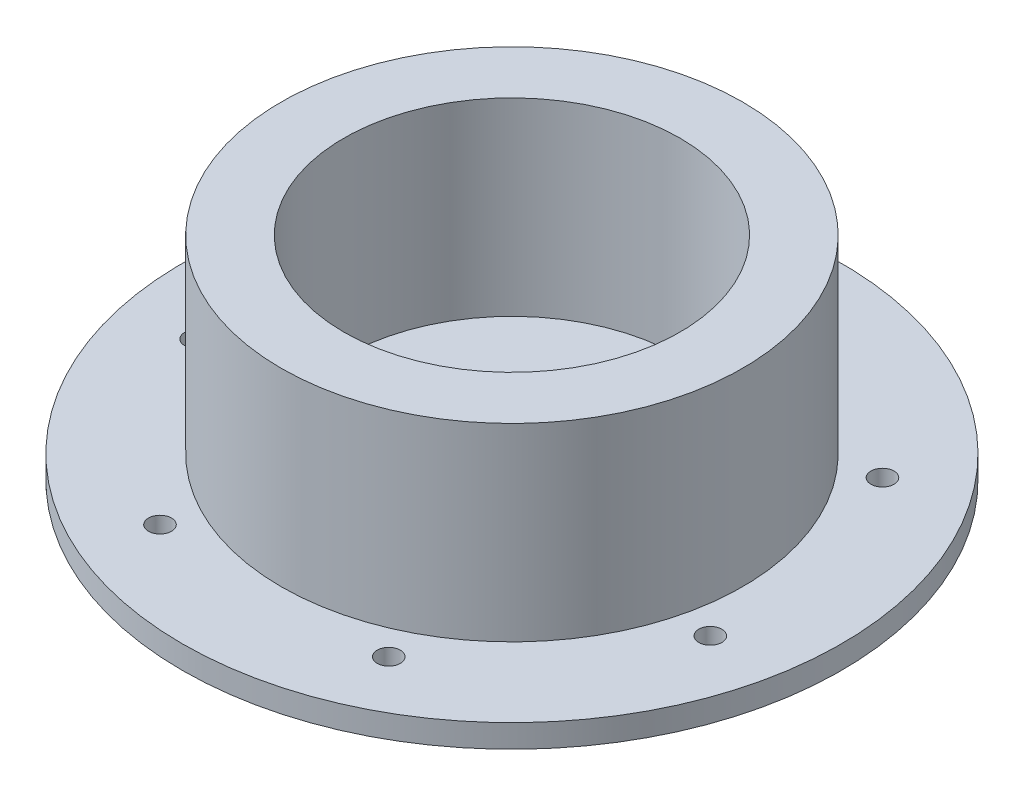
SolidWorks part; units mm, degrees
material "Cast Alloy Steel"
ref_plane "Front Plane" through (0, 0, 0) normal (0, 0, 1) x (1, 0, 0)
ref_plane "Top Plane" through (0, 0, 0) normal (0, 1, 0) x (1, 0, 0)
ref_plane "Right Plane" through (0, 0, 0) normal (1, 0, 0) x (0, 0, -1)
sketch "Sketch1" plane through (0, 0, 0) normal (0, 1, 0) x (1, 0, 0)
  circle A0 centre (0, 0) radius 50
  circle A1 centre (0, 40) radius 1.75
  circle A2 centre (31.2733, 24.9396) radius 1.75
  circle A3 centre (38.9971, -8.9008) radius 1.75
  circle A4 centre (17.3553, -36.0388) radius 1.75
  circle A5 centre (-17.3553, -36.0388) radius 1.75
  circle A6 centre (-38.9971, -8.9008) radius 1.75
  circle A7 centre (-31.2733, 24.9396) radius 1.75
  point P19 (0, 0)
  dimension "D1" = 40
  dimension "D2" = 100
  dimension "D3" = 3.5
  dimension "D4" = 7
extrude "Boss-Extrude1" add sketch "Sketch1" along normal blind 3.5
sketch "Sketch2" plane through (0, 3.5, 0) normal (0, 1, 0) x (1, 0, 0)
  circle A0 centre (0, 0) radius 35
  circle A1 centre (0, 0) radius 25.5
  dimension "D1" = 70
  dimension "D2" = 51
extrude "Boss-Extrude3" add sketch "Sketch2" along normal blind 28.7 contours A1
